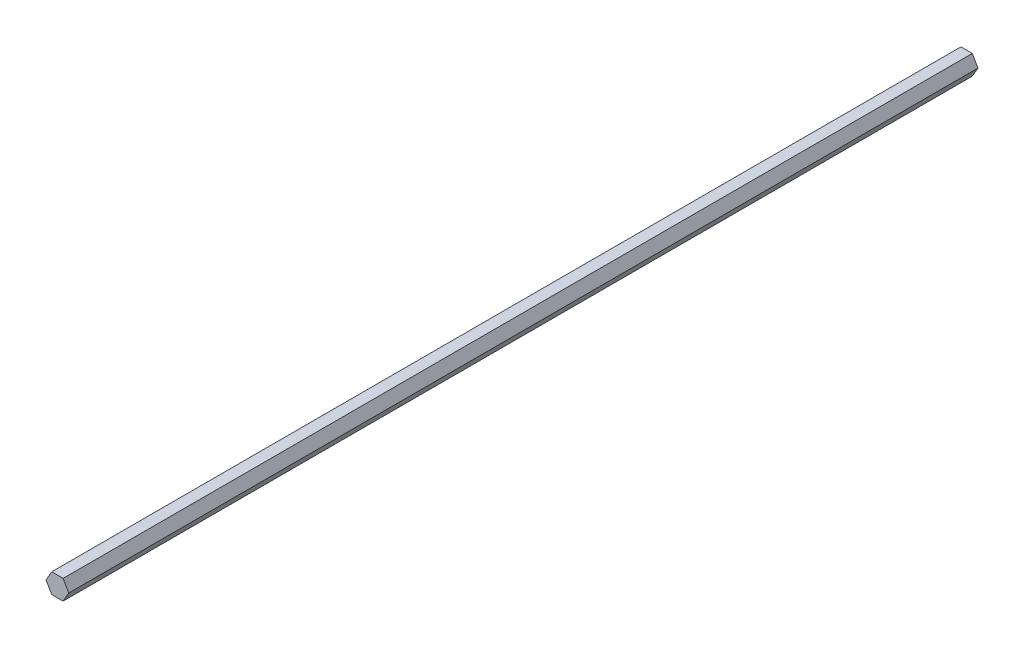
SolidWorks part; units mm, degrees
ref_plane "Front Plane" through (0, 0, 0) normal (0, 0, 1) x (1, 0, 0)
ref_plane "Top Plane" through (0, 0, 0) normal (0, 1, 0) x (1, 0, 0)
ref_plane "Right Plane" through (0, 0, 0) normal (1, 0, 0) x (0, 0, -1)
sketch "Sketch1" plane through (0, 0, 0) normal (0, 0, 1) x (1, 0, 0)
  line L1 (3.6662, -6.35) -> (7.3323, 0)
  line L2 (7.3323, 0) -> (3.6662, 6.35)
  line L3 (3.6662, 6.35) -> (-3.6662, 6.35)
  line L4 (-3.6662, 6.35) -> (-7.3323, 0)
  line L5 (-7.3323, 0) -> (-3.6662, -6.35)
  line L6 (-3.6662, -6.35) -> (3.6662, -6.35)
  circle A0 centre (0, 0) radius 6.35 construction
  dimension "D1" = 12.7
extrude "Boss-Extrude1" add sketch "Sketch1" along normal mid plane 585.7875
